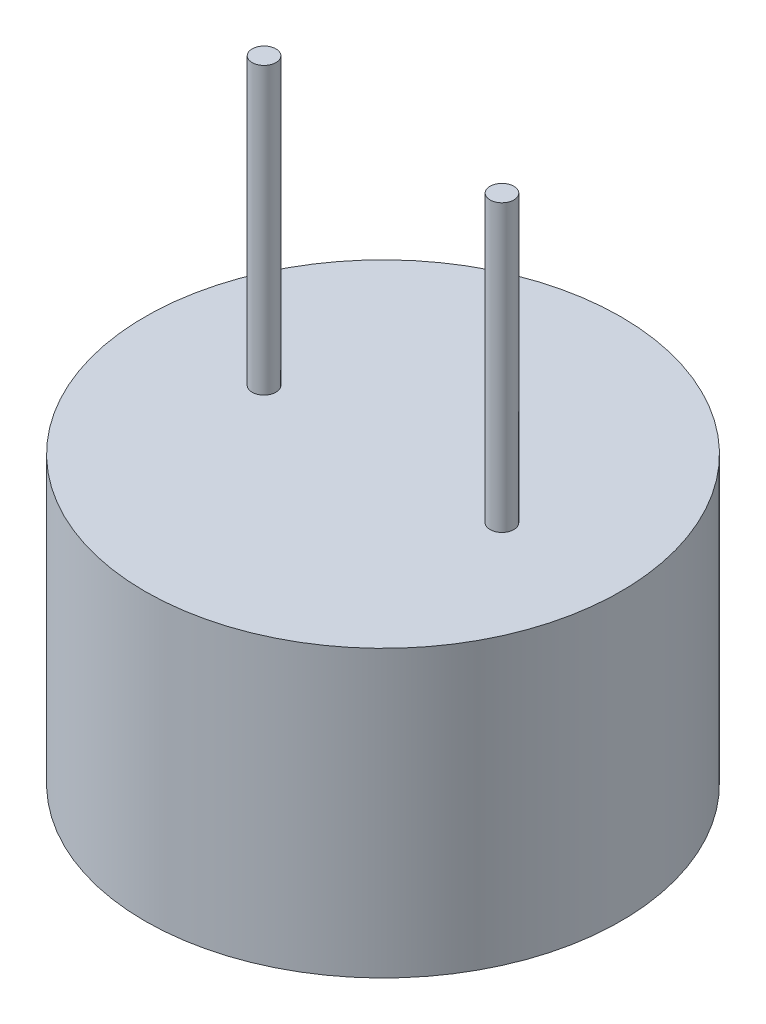
SolidWorks part; units mm, degrees
ref_plane "Спереди" through (0, 0, 0) normal (0, 0, 1) x (1, 0, 0)
ref_plane "Сверху" through (0, 0, 0) normal (0, 1, 0) x (1, 0, 0)
ref_plane "Справа" through (0, 0, 0) normal (1, 0, 0) x (0, 0, -1)
sketch "Эскиз1" plane through (0, 0, 0) normal (0, 1, 0) x (1, 0, 0)
  circle A0 centre (0, 0) radius 5
  dimension "D1" = 10
extrude "Бобышка-Вытянуть1" add sketch "Эскиз1" along normal blind 6
sketch "Эскиз2" plane through (0, 6, 0) normal (0, 1, 0) x (1, 0, 0)
  line L0 (0, 5) -> (0, -5) construction
  line L1 (-5, 0) -> (5, 0) construction
  circle A0 centre (0, 0) radius 5 construction
  circle A1 centre (-2.5, 0) radius 0.25
  circle A2 centre (2.5, 0) radius 0.25
  dimension "D1" = 0.5
  dimension "D2" = 2.5
extrude "Бобышка-Вытянуть2" add sketch "Эскиз2" along normal blind 6
